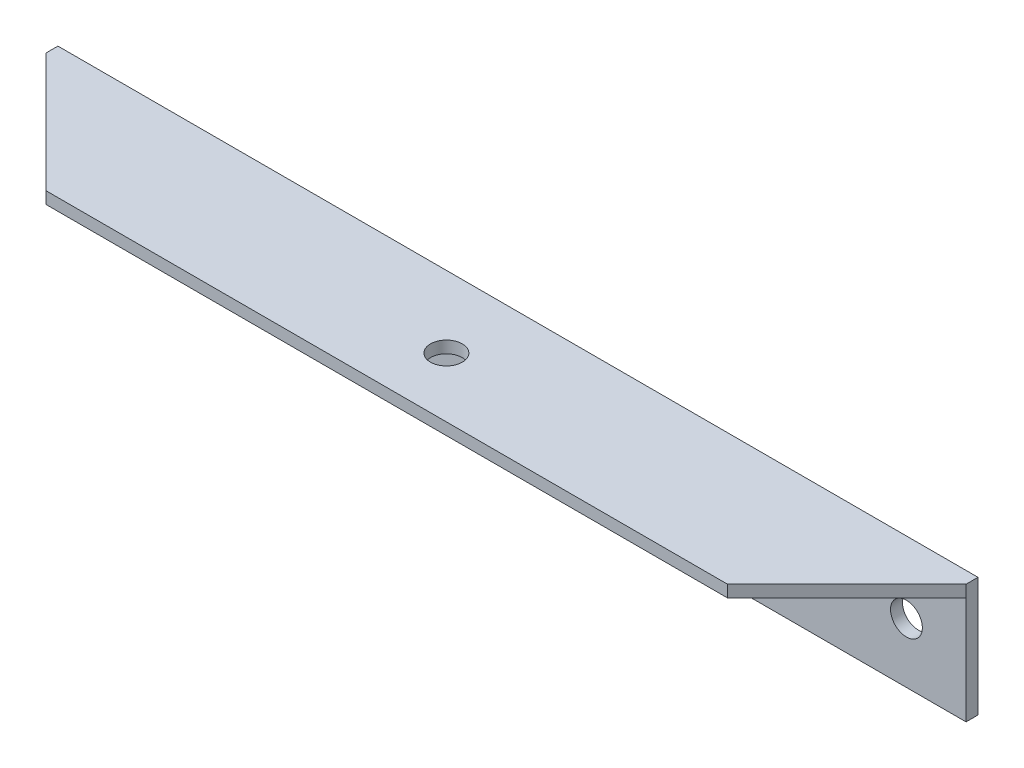
SolidWorks part; units mm, degrees
ref_plane "Front Plane" through (0, 0, 0) normal (0, 0, 1) x (1, 0, 0)
ref_plane "Top Plane" through (0, 0, 0) normal (0, 1, 0) x (1, 0, 0)
ref_plane "Right Plane" through (0, 0, 0) normal (1, 0, 0) x (0, 0, -1)
sketch "Sketch1" plane through (0, 0, 0) normal (0, 0, 1) x (1, 0, 0)
  line L0 (-115.7, 0) -> (115.7, 0)
  line L1 (-115.7, 0) -> (-115.7, -30)
  line L2 (115.7, 0) -> (115.7, -30)
  line L3 (-115.7, -30) -> (115.7, -30)
  point P4 (0, 0)
  dimension "D1" = 231.4
  dimension "D2" = 30
  dimension "D3" = 30
extrude "Boss-Extrude1" add sketch "Sketch1" along normal blind 3
sketch "Sketch3" plane through (0, 0, 0) normal (0, 1, 0) x (1, 0, 0)
  line L2 (-85.7, -33) -> (85.7, -33)
  line L3 (-115.7, -3) -> (115.7, -3)
  line L4 (-115.7, -3) -> (-85.7, -33)
  line L5 (115.7, -3) -> (85.7, -33)
  dimension "D1" = 30
  dimension "D3" = 45
  dimension "D4" = 45
extrude "Boss-Extrude2" add sketch "Sketch3" against normal blind 3
sketch "Sketch9" plane through (0, 0, 0) normal (0, 0, -1) x (-1, 0, 0)
  line L0 (115.7, 0) -> (100.7, 0) construction
  line L1 (-115.7, 0) -> (115.7, 0) construction
  line L2 (100.7, 0) -> (100.7, -15) construction
  line L3 (-115.7, 0) -> (-100.7, 0) construction
  line L4 (-100.7, 0) -> (-100.7, -15) construction
  dimension "D1" = 15
  dimension "D2" = 15
  dimension "D3" = 15
  dimension "D4" = 15
hole_wizard "Ø8.0 (8) Diameter Hole2" positions "Sketch10" profile "Sketch11" hole size "Ø8.0" standard "AS" end condition through all
sketch "Sketch10" plane through (0, 0, 0) normal (0, 0, -1) x (-1, 0, 0)
  point P0 (100.7, -15)
  point P3 (-100.7, -15)
sketch "Sketch11" plane through (-100.7, -15, 0) normal (1, 0, 0) x (0, 1, 0)
  line L0 (0, 0) -> (0, 33)
  line L1 (0, 33) -> (4, 33)
  line L2 (4, 33) -> (4, 0)
  line L5 (4, 0) -> (0, 0)
  line L11 (0, -6.35) -> (0, 107.95) construction
  dimension "Thru Hole Dia." = 8
  dimension "Thru Hole Depth" = 33
sketch "Sketch12" plane through (0, -3, 0) normal (0, -1, 0) x (1, 0, 0)
  line L1 (-85.7, 33) -> (85.7, 33) construction
  line L2 (-85.7, 33) -> (85.7, 33) construction
  line L3 (0, 33) -> (0, 18) construction
  dimension "D1" = 15
hole_wizard "Ø8.0 (8) Diameter Hole1" positions "Sketch13" profile "Sketch14" hole size "Ø8.0" standard "AS" end condition through all
sketch "Sketch13" plane through (0, -3, 0) normal (0, -1, 0) x (-1, 0, 0)
  point P0 (0, -18)
sketch "Sketch14" plane through (0, -3, 18) normal (1, 0, 0) x (0, 0, -1)
  line L0 (0, 0) -> (0, 3)
  line L1 (0, 3) -> (4, 3)
  line L2 (4, 3) -> (4, 0)
  line L5 (4, 0) -> (0, 0)
  line L11 (0, -6.35) -> (0, 107.95) construction
  dimension "Thru Hole Dia." = 8
  dimension "Thru Hole Depth" = 3
